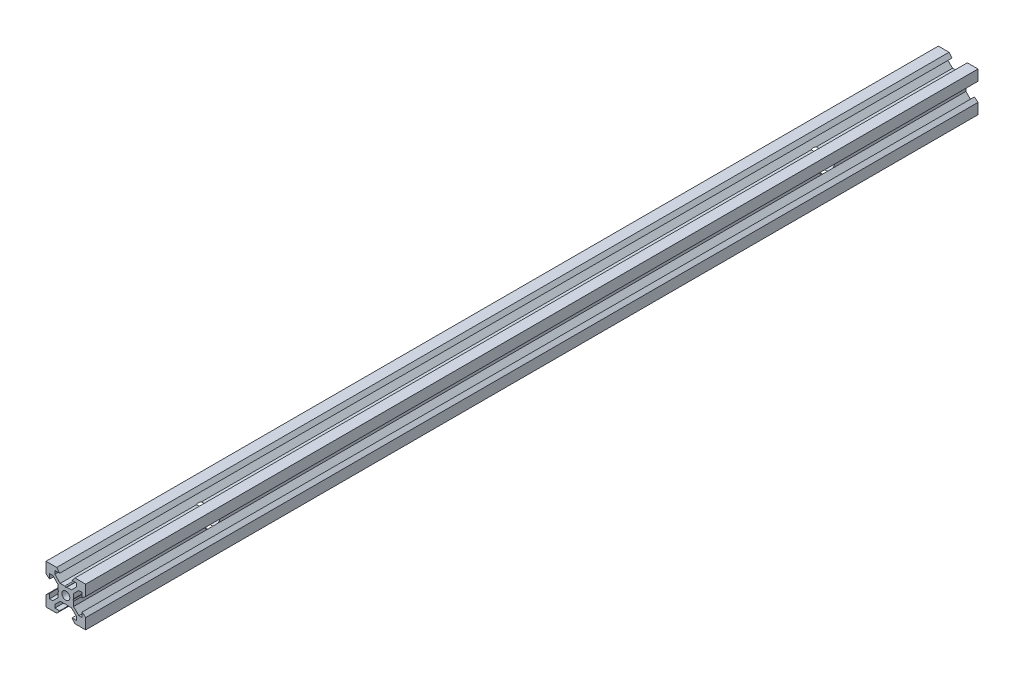
SolidWorks part; units mm, degrees
material "1060 Alloy"
ref_plane "Front Plane" through (0, 0, 0) normal (0, 0, 1) x (1, 0, 0)
ref_plane "Top Plane" through (0, 0, 0) normal (0, 1, 0) x (1, 0, 0)
ref_plane "Right Plane" through (0, 0, 0) normal (1, 0, 0) x (0, 0, -1)
sketch "Sketch1" plane through (0, 0, 0) normal (0, 0, 1) x (1, 0, 0)
  line L0 (10, 10) -> (4.6104, 10) construction
  line L1 (10, 10) -> (10, 4.6104) construction
  line L2 (10, -10) -> (10, -4.6104) construction
  line L3 (10, -10) -> (4.6104, -10) construction
  line L4 (10, 10) -> (10, 4.6104)
  line L5 (6.5607, 5.5) -> (8.2, 5.5)
  line L6 (5.5, 8.2) -> (5.5, 6.5607)
  line L7 (10, 10) -> (4.6104, 10)
  line L8 (10, 10) -> (10, 4.6104)
  line L9 (6.5607, 5.5) -> (3.9, 2.8393)
  line L10 (5.5, 6.5607) -> (2.8393, 3.9)
  line L11 (10, 4.6104) -> (8.2, 3.1)
  line L12 (4.6104, 10) -> (3.1, 8.2)
  line L13 (8.2, 3.1) -> (8.2, 5.5)
  line L14 (3.1, 8.2) -> (5.5, 8.2)
  line L15 (-6.5607, 5.5) -> (-8.2, 5.5)
  line L16 (6.5607, -5.5) -> (8.2, -5.5)
  line L17 (3.1, -8.2) -> (5.5, -8.2)
  line L18 (8.2, -3.1) -> (8.2, -5.5)
  line L19 (4.6104, -10) -> (3.1, -8.2)
  line L20 (10, -4.6104) -> (8.2, -3.1)
  line L21 (0.5196, -3.9) -> (0, -3.6)
  line L22 (0.5196, 3.9) -> (0, 3.6)
  line L23 (3.6, 0) -> (3.9, -0.5196)
  line L24 (3.9, 0.5196) -> (3.6, 0)
  line L25 (3.9, 0.5196) -> (3.9, 2.8393)
  line L26 (2.8393, 3.9) -> (0.5196, 3.9)
  line L27 (3.9, -2.8393) -> (3.9, -0.5196)
  line L28 (2.8393, -3.9) -> (0.5196, -3.9)
  line L29 (5.5, -6.5607) -> (2.8393, -3.9)
  line L30 (6.5607, -5.5) -> (3.9, -2.8393)
  line L31 (10, -10) -> (10, -4.6104)
  line L32 (10, -10) -> (4.6104, -10)
  line L33 (5.5, -8.2) -> (5.5, -6.5607)
  line L34 (-6.5607, -5.5) -> (-8.2, -5.5)
  line L35 (10, -10) -> (10, -4.6104)
  line L36 (0, 0) -> (0, 8.2) construction
  line L37 (-10, -10) -> (-4.6104, -10) construction
  line L38 (-10, -10) -> (-10, -4.6104) construction
  line L39 (-10, 10) -> (-10, 4.6104) construction
  line L40 (-10, 10) -> (-4.6104, 10) construction
  line L41 (-10, -10) -> (-10, -4.6104)
  line L43 (-5.5, -8.2) -> (-5.5, -6.5607)
  line L44 (-10, -10) -> (-4.6104, -10)
  line L45 (-10, -10) -> (-10, -4.6104)
  line L46 (-6.5607, -5.5) -> (-3.9, -2.8393)
  line L47 (-5.5, -6.5607) -> (-2.8393, -3.9)
  line L48 (-2.8393, -3.9) -> (-0.5196, -3.9)
  line L49 (-3.9, -2.8393) -> (-3.9, -0.5196)
  line L50 (-2.8393, 3.9) -> (-0.5196, 3.9)
  line L51 (-3.9, 0.5196) -> (-3.9, 2.8393)
  line L52 (-3.9, 0.5196) -> (-3.6, 0)
  line L53 (-3.6, 0) -> (-3.9, -0.5196)
  line L54 (-0.5196, 3.9) -> (0, 3.6)
  line L55 (-0.5196, -3.9) -> (0, -3.6)
  line L56 (-10, -4.6104) -> (-8.2, -3.1)
  line L57 (-4.6104, -10) -> (-3.1, -8.2)
  line L58 (-8.2, -3.1) -> (-8.2, -5.5)
  line L59 (-3.1, -8.2) -> (-5.5, -8.2)
  line L60 (-10, -10) -> (10, -10) construction
  line L61 (-10, -10) -> (-10, 10) construction
  line L62 (-3.1, 8.2) -> (-5.5, 8.2)
  line L63 (-8.2, 3.1) -> (-8.2, 5.5)
  line L64 (-4.6104, 10) -> (-3.1, 8.2)
  line L65 (-10, 4.6104) -> (-8.2, 3.1)
  line L66 (-5.5, 6.5607) -> (-2.8393, 3.9)
  line L67 (-6.5607, 5.5) -> (-3.9, 2.8393)
  line L68 (-10, 10) -> (-10, 4.6104)
  line L69 (-10, 10) -> (-4.6104, 10)
  line L70 (-5.5, 8.2) -> (-5.5, 6.5607)
  line L71 (-10, 10) -> (10, 10) construction
  line L72 (-10, 10) -> (-10, 4.6104)
  line L73 (10, -10) -> (10, 10) construction
  line L74 (-10, -10) -> (10, 10) construction
  line L75 (-10, 10) -> (10, -10) construction
  circle A0 centre (0, 0) radius 2
  dimension "D7" = 4
  dimension "D1" = 20
  dimension "D2" = 5.3896
  dimension "D3" = 4.5
  dimension "D4" = 50
  dimension "D5" = 1.8
  dimension "D6" = 1.5104
  dimension "D8" = 5.5
  dimension "D9" = 120
  dimension "D10" = 0.3
  dimension "D11" = 2.3197
  dimension "D12" = 7.8
  dimension "D13" = 7.8
  dimension "D14" = 1.5
  dimension "D15" = 2.6607
extrude "Boss-Extrude1" add sketch "Sketch1" along normal blind 450 contours L70 L62 L64 L69 L68 L65 L63 L15 L67 L51 L52 L53 L49 L46 L34 L58 L56 L41 L44 L57 L59 L43 L47 L48 L55 L21 L28 L29 L33 L17 L19 L32 L31 L20 L18 L16 L30 L27 L23 L24 L25 L9 L5 L13 L11 L4 L7 L12 L14 L6 L10
sketch "Sketch2" plane through (3.9, 0, 0) normal (1, 0, 0) x (0, 0, -1)
  line L0 (-450, -0.5196) -> (-380, -0.5196) construction
  line L1 (-450, -0.5196) -> (0, -0.5196) construction
  line L2 (-380, -0.5196) -> (-380, 0) construction
  line L3 (0, -0.5196) -> (-70, -0.5196) construction
  line L4 (-380, 0) -> (-70, 0) construction
  line L5 (-70, 0) -> (-70, -0.5196) construction
  circle A0 centre (-380, 0) radius 4.1
  circle A1 centre (-70, 0) radius 4.1
  dimension "D2" = 8.2
  dimension "D4" = 8.2
  dimension "D1" = 70
  dimension "D3" = 70
extrude "Cut-Extrude1" cut sketch "Sketch2" against normal through all
